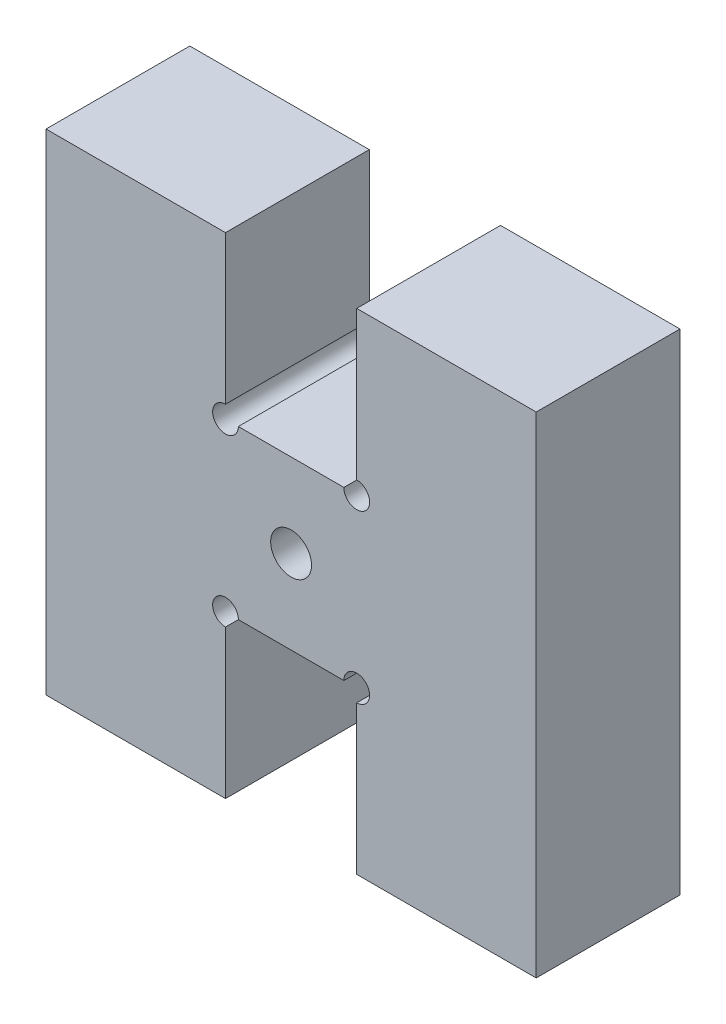
SolidWorks part; units mm, degrees
ref_plane "Front Plane" through (0, 0, 0) normal (0, 0, 1) x (1, 0, 0)
ref_plane "Top Plane" through (0, 0, 0) normal (0, 1, 0) x (1, 0, 0)
ref_plane "Right Plane" through (0, 0, 0) normal (1, 0, 0) x (0, 0, -1)
sketch "Sketch1" plane through (0, 0, 0) normal (0, 0, 1) x (1, 0, 0)
  line L0 (-2.55, 3.25) -> (-2.55, 9.525)
  line L1 (-2.55, 3.25) -> (2.55, 3.25)
  line L3 (-2.55, -3.25) -> (2.55, -3.25)
  line L5 (-2.55, 9.525) -> (-9.525, 9.525)
  line L6 (-9.525, 9.525) -> (-9.525, -9.525)
  line L7 (-9.525, -9.525) -> (-2.55, -9.525)
  line L8 (-2.55, -9.525) -> (-2.55, -3.25)
  line L9 (2.55, -3.25) -> (2.55, -9.525)
  line L10 (2.55, -9.525) -> (9.525, -9.525)
  line L11 (9.525, -9.525) -> (9.525, 9.525)
  line L12 (9.525, 9.525) -> (2.55, 9.525)
  line L13 (2.55, 9.525) -> (2.55, 3.25)
  line L14 (0, 3.25) -> (0, -3.25) construction
  circle A0 centre (0, 0) radius 0.7937
  dimension "D5" = 1.5875
  dimension "D1" = 5.1
  dimension "D2" = 19.05
  dimension "D3" = 19.05
  dimension "D4" = 6.5
extrude "Boss-Extrude1" add sketch "Sketch1" along normal blind 5.588
sketch "Sketch2" plane through (0, 0, 0) normal (0, 0, 1) x (1, 0, 0)
  circle A0 centre (-2.55, 3.25) radius 0.5
  circle A1 centre (2.55, 3.25) radius 0.5
  circle A2 centre (2.55, -3.25) radius 0.5
  circle A3 centre (-2.55, -3.25) radius 0.5
  dimension "D1" = 1
extrude "Cut-Extrude2" cut sketch "Sketch2" along normal through all both and the other way through all
